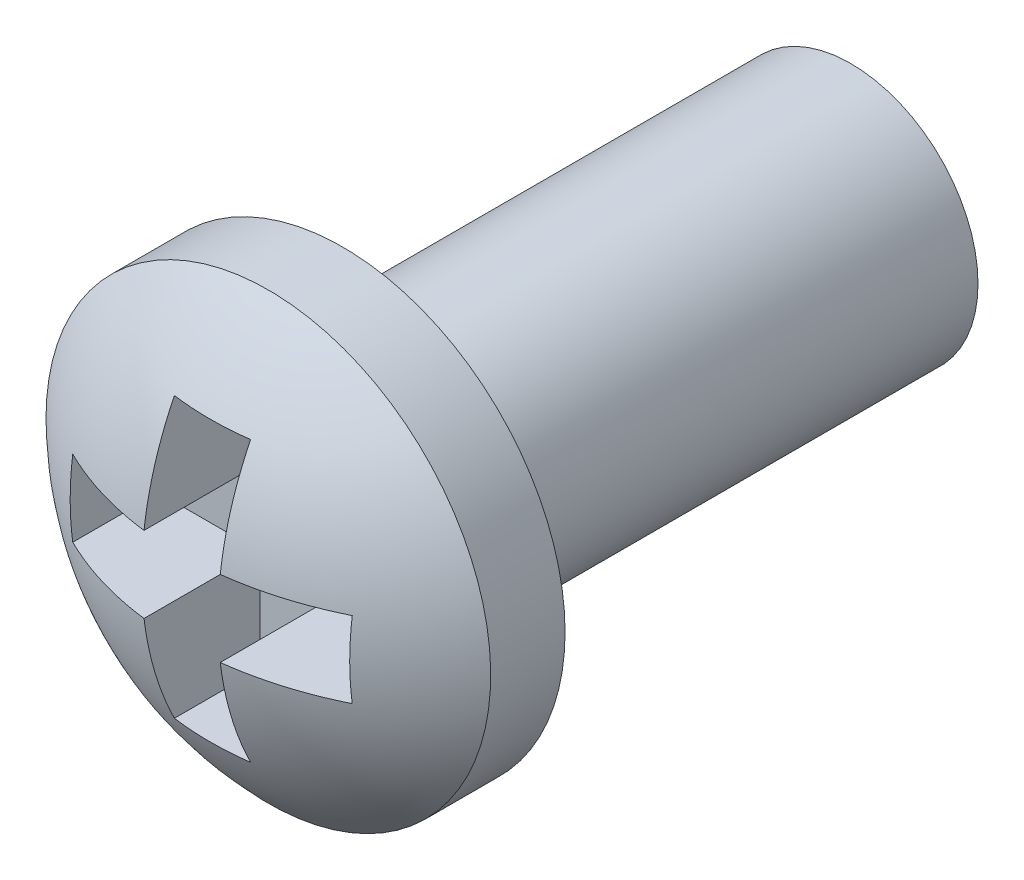
SolidWorks part; units mm, degrees
ref_plane "前视基准面" through (0, 0, 0) normal (0, 0, 1) x (1, 0, 0)
ref_plane "上视基准面" through (0, 0, 0) normal (0, 1, 0) x (1, 0, 0)
ref_plane "右视基准面" through (0, 0, 0) normal (1, 0, 0) x (0, 0, -1)
other "Configuration Table"
sketch "草图1" plane through (0, 0, 0) normal (0, 0, 1) x (1, 0, 0)
  circle A0 centre (0, 0) radius 1
extrude "标准杆径_头下长度" add sketch "草图1" against normal blind 4
sketch "草图2" plane through (0, 0, 0) normal (0, 0, 1) x (1, 0, 0)
  circle A0 centre (0, 0) radius 1.9
sketch "草图4" plane through (0, 0, 0) normal (0, 1, 0) x (1, 0, 0)
  line L0 (0, 0) -> (2.25, 0)
  line L1 (2.25, 0) -> (2.25, -0.1843)
  line L2 (0, -1.2) -> (0, 0)
  line L3 (0, 2) -> (0, -3.2) construction
  arc A0 (2.25, -0.1843) -> (0, -1.2) centre (0, 1.8) cw
sketch "草图5" plane through (0, 0, 0) normal (0, 0, 1) x (1, 0, 0)
  line L0 (-0.3, -1.1) -> (0.3, -1.1)
  line L1 (0.3, -1.1) -> (0.3, -0.3)
  line L2 (0.3, -0.3) -> (1.1, -0.3)
  line L3 (1.1, -0.3) -> (1.1, 0.3)
  line L4 (1.1, 0.3) -> (0.3, 0.3)
  line L5 (0.3, 0.3) -> (0.3, 1.1)
  line L6 (0.3, 1.1) -> (-0.3, 1.1)
  line L7 (-0.3, 1.1) -> (-0.3, 0.3)
  line L8 (-0.3, 0.3) -> (-1.1, 0.3)
  line L9 (-1.1, 0.3) -> (-1.1, -0.3)
  line L10 (-1.1, -0.3) -> (-0.3, -0.3)
  line L11 (-0.3, -0.3) -> (-0.3, -1.1)
sketch "草图6" plane through (0, 0, 0) normal (0, 1, 0) x (1, 0, 0)
  line L0 (0, 0) -> (1.75, 0)
  line L1 (1.75, 0) -> (1.75, -0.5854)
  line L2 (0, -1.3) -> (0, 0)
  line L3 (0, 2) -> (0, -3.3) construction
  arc A0 (1.75, -0.5854) -> (0, -1.3) centre (0, 1.2) cw
revolve "已确认_十字槽盘头" add sketch "草图6" angle 360 about L3
sketch "草图7" plane through (0, 0, 0) normal (0, 0, 1) x (1, 0, 0)
  line L0 (-0.3, -1.1) -> (0.3, -1.1)
  line L1 (0.3, -1.1) -> (0.3, -0.3)
  line L2 (0.3, -0.3) -> (1.1, -0.3)
  line L3 (1.1, -0.3) -> (1.1, 0.3)
  line L4 (1.1, 0.3) -> (0.3, 0.3)
  line L5 (0.3, 0.3) -> (0.3, 1.1)
  line L6 (0.3, 1.1) -> (-0.3, 1.1)
  line L7 (-0.3, 1.1) -> (-0.3, 0.3)
  line L8 (-0.3, 0.3) -> (-1.1, 0.3)
  line L9 (-1.1, 0.3) -> (-1.1, -0.3)
  line L10 (-1.1, -0.3) -> (-0.3, -0.3)
  line L11 (-0.3, -0.3) -> (-0.3, -1.1)
extrude "十字槽_PH1_简化" cut sketch "草图7" against normal blind 0.96 from offset 1.31
